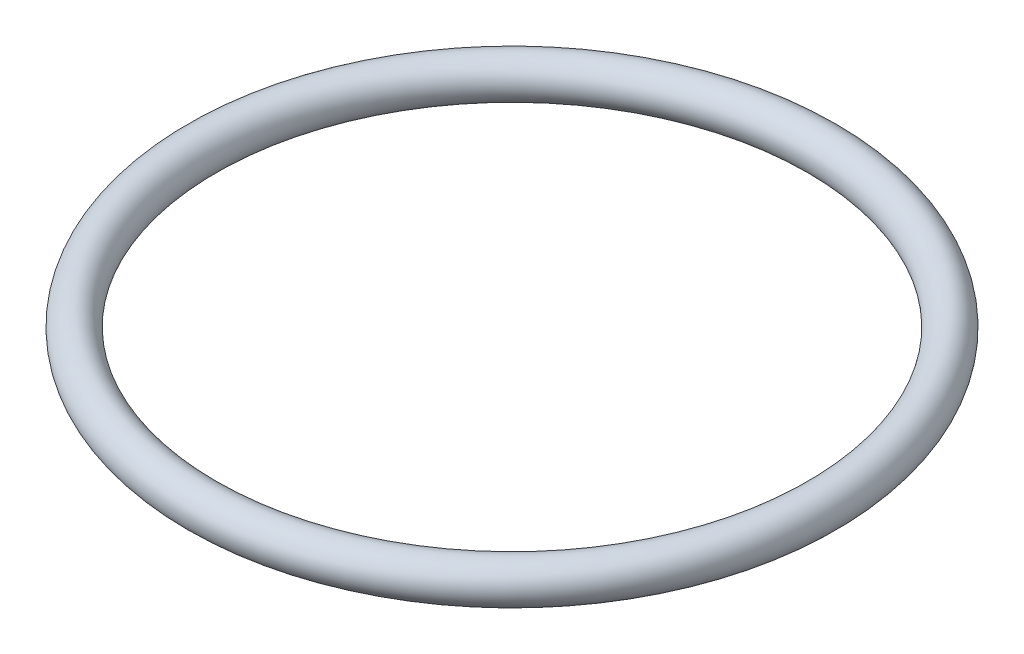
SolidWorks part; units mm, degrees
material "VITON"
ref_plane "Front Plane" through (0, 0, 0) normal (0, 0, 1) x (1, 0, 0)
ref_plane "Top Plane" through (0, 0, 0) normal (0, 1, 0) x (1, 0, 0)
ref_plane "Right Plane" through (0, 0, 0) normal (1, 0, 0) x (0, 0, -1)
sketch "Sketch1" plane through (0, 0, 0) normal (0, 0, 1) x (1, 0, 0)
  line L0 (0, 0) -> (0, 6.5809) construction
  circle A0 centre (-19.45, 0) radius 1.25
  dimension "D1" = 2.5
  dimension "D2" = 19.45
revolve "Revolve1" add sketch "Sketch1" angle 360 about L0
